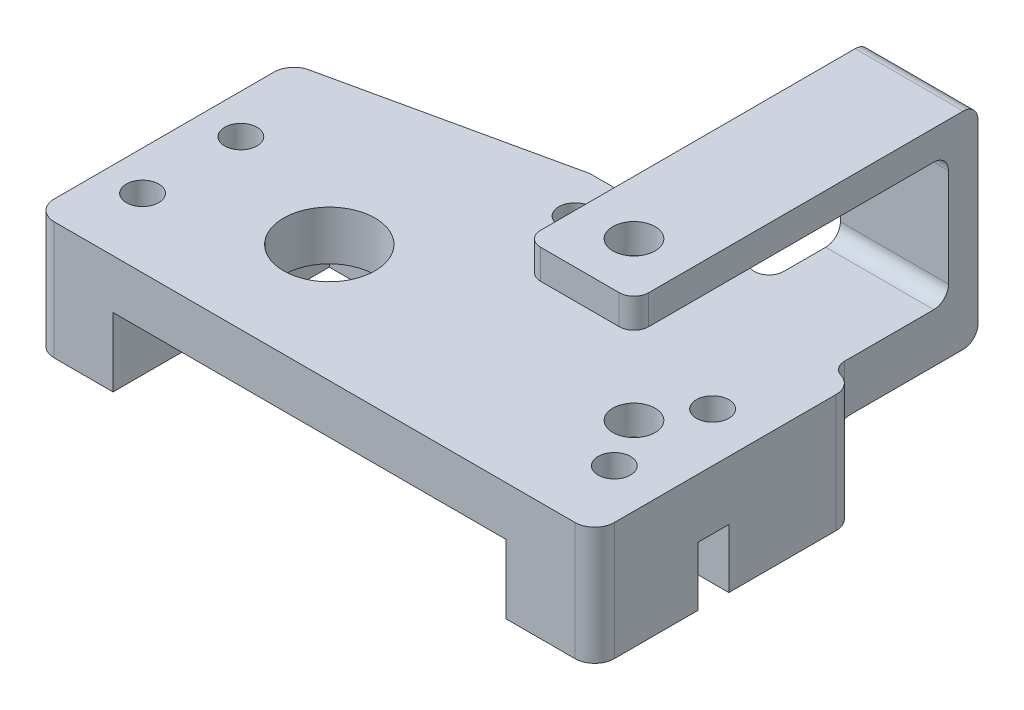
SolidWorks part; units mm, degrees
other "标注1"
sketch "草图14" plane through (64, 22, 26) normal (0.1348, 0.9386, 0.3174) x (-0.9379, 0.0175, 0.3464)
ref_plane "前视基准面" through (0, 0, 0) normal (0, 0, 1) x (1, 0, 0)
ref_plane "上视基准面" through (0, 0, 0) normal (0, 1, 0) x (1, 0, 0)
ref_plane "右视基准面" through (0, 0, 0) normal (1, 0, 0) x (0, 0, -1)
sketch "草图1" plane through (0, 0, 0) normal (0, 1, 0) x (1, 0, 0)
  line L0 (0, 0) -> (25, 5.5)
  line L2 (0, 0) -> (0, -26)
  line L3 (0, -26) -> (8, -26)
  line L4 (57, 0) -> (57, -26)
  line L7 (25, 5.5) -> (41, 5.5)
  line L10 (8, -26) -> (8, -4)
  line L11 (8, -4) -> (48, -4)
  line L12 (48, -26) -> (48, -17)
  line L13 (41, 5.5) -> (57, 0)
  line L14 (48, -26) -> (57, -26)
  line L15 (48, -11) -> (48, -4)
  circle A0 centre (4, -9) radius 1.65
  circle A1 centre (4, -19) radius 1.65
  circle A2 centre (52, -9) radius 1.65
  circle A3 centre (52, -19) radius 1.65
  circle A4 centre (28, 1) radius 1.65
  circle A5 centre (38, 1) radius 1.65
  arc A6 (48, -17) -> (48, -11) centre (49, -14) ccw
  point P12 (25, 5.5)
  point P13 (41, 5.5)
  point P14 (25, 5.5)
  point P15 (0, 0)
  dimension "D6" = 17
  dimension "D7" = 4
  dimension "D8" = 2
  dimension "D10" = 5
  dimension "D11" = 2
  dimension "D12" = 10
  dimension "D13" = 3.3
  dimension "D14" = 48
  dimension "D1" = 26
  dimension "D2" = 57
  dimension "D3" = 40
  dimension "D4" = 22
  dimension "D5" = 8
  dimension "D9" = 2
extrude "凸台-拉伸1" add sketch "草图1" along normal blind 12
sketch "草图2" plane through (0, 0, 0) normal (0, -1, 0) x (-1, 0, 0)
  line L1 (-26.6144, -1.4) -> (-25.2287, 1)
  line L2 (-25.2287, 1) -> (-26.6144, 3.4)
  line L3 (-26.6144, 3.4) -> (-29.3856, 3.4)
  line L4 (-29.3856, 3.4) -> (-30.7713, 1)
  line L5 (-30.7713, 1) -> (-29.3856, -1.4)
  line L6 (-29.3856, -1.4) -> (-26.6144, -1.4)
  line L8 (-41, 5.5) -> (-25, 5.5) construction
  line L9 (-36.6144, -1.4) -> (-35.2287, 1)
  line L10 (-35.2287, 1) -> (-36.6144, 3.4)
  line L11 (-36.6144, 3.4) -> (-39.3856, 3.4)
  line L12 (-39.3856, 3.4) -> (-40.7713, 1)
  line L13 (-40.7713, 1) -> (-39.3856, -1.4)
  line L14 (-39.3856, -1.4) -> (-36.6144, -1.4)
  circle A0 centre (-28, 1) radius 2.4 construction
  dimension "D2" = 4.8
  dimension "D1" = 2
extrude "切除-拉伸1" cut sketch "草图2" against normal blind 8
fillet "圆角1" radius 2 6 edges at (57, 6, 26) (57, 6, 0) (41, 6, -5.5) (25, 6, -5.5) (0, 6, 0) (0, 6, 26)
sketch "草图5" plane through (0, 12, 0) normal (0, 1, 0) x (1, 0, 0)
  line L0 (48, -11) -> (48, -4)
  line L1 (8, -26) -> (48, -26)
  line L2 (8, -26) -> (8, -4)
  line L3 (8, -4) -> (48, -4)
  line L4 (48, -26) -> (48, -17)
  line L5 (0, -1.6078) -> (0, -24) construction
  arc A0 (48, -17) -> (48, -11) centre (49, -14) ccw
  circle A1 centre (28, 1) radius 1.55
  circle A2 centre (38, 1) radius 1.55
  circle A3 centre (49, -14) radius 1.55
  circle A4 centre (18, -14) radius 4.6563
  dimension "D1" = 12
  dimension "D2" = 18
extrude "凸台-拉伸3" add sketch "草图5" against normal blind 5 separate body
sketch "草图6" plane through (0, 7, 0) normal (0, -1, 0) x (-1, 0, 0)
  circle A0 centre (-28, 1) radius 1.55
  circle A1 centre (-38, 1) radius 1.55
sketch "草图7" plane through (0, 7, 0) normal (0, -1, 0) x (-1, 0, 0)
  circle A0 centre (-49, -14) radius 3.15
extrude "切除-拉伸2" cut sketch "草图7" against normal blind 2
sketch "草图8" plane through (0, 0, 0) normal (0, -1, 0) x (-1, 0, 0)
  line L0 (-57, -24) -> (-57, -1.4274) construction
  line L1 (-8, -15.162) -> (0, -15.162)
  line L2 (-8, -15.162) -> (-8, -12.162)
  line L3 (-8, -12.162) -> (0, -12.162)
  line L4 (0, -15.162) -> (0, -12.162)
  line L5 (-51.7, -12.3538) -> (-57, -12.3538)
  line L6 (-51.7, -12.3538) -> (-51.7, -15.4875)
  line L7 (-51.7, -15.4875) -> (-57, -15.4875)
  line L8 (-57, -12.3538) -> (-57, -15.4875)
  line L9 (-8, -26) -> (-8, -4) construction
  arc A0 (-48, -11) -> (-48, -17) centre (-49, -14) ccw construction
  dimension "D2" = 8
  dimension "D1" = 3
extrude "切除-拉伸3" cut sketch "草图8" against normal blind 6
extrude "切除-拉伸4" cut sketch "草图6" against normal blind 10
sketch "草图17" plane through (0, 0, -5.5) normal (0, 0, -1) x (-1, 0, 0)
  line L0 (-55.6502, 12) -> (-41.316, 12) construction
  line L1 (-43.5, 12) -> (-54.5, 12)
  line L2 (-43.5, 12) -> (-43.5, 9)
  line L3 (-43.5, 9) -> (-54.5, 7)
  line L4 (-54.5, 12) -> (-54.5, 7)
  dimension "D1" = 3
extrude "凸台-拉伸9" add sketch "草图17" along normal blind 10 and the other way blind 10
sketch "草图18" plane through (0, 12, 0) normal (0, 1, 0) x (1, 0, 0)
  line L0 (54.5, 0.8594) -> (54.5, 15.5) construction
  line L1 (43.5, 15.5) -> (54.5, 15.5)
  line L2 (43.5, 15.5) -> (43.5, 12.5)
  line L3 (43.5, 12.5) -> (54.5, 12.5)
  line L4 (54.5, 15.5) -> (54.5, 12.5)
  dimension "D1" = 3
extrude "凸台-拉伸10" add sketch "草图18" along normal blind 16
sketch "草图19" plane through (0, 0, -12.5) normal (0, 0, 1) x (1, 0, 0)
  line L0 (54.5, 28) -> (54.5, 12) construction
  line L1 (43.5, 28) -> (54.5, 28)
  line L2 (43.5, 28) -> (43.5, 25)
  line L3 (43.5, 25) -> (54.5, 25)
  line L4 (54.5, 28) -> (54.5, 25)
  dimension "D1" = 3
extrude "凸台-拉伸11" add sketch "草图19" along normal blind 32
sketch "草图20" plane through (0, 28, 0) normal (0, 1, 0) x (1, 0, 0)
  circle A0 centre (49, -14) radius 2.15
  circle A1 centre (49, -14) radius 1.55 construction
extrude "切除-拉伸7" cut sketch "草图20" against normal blind 22
fillet "圆角4" radius 1.5 9 edges at (54.5, 9.5, -0.8594) (54.5, 26.5, 19.5) (43.5, 26.5, 19.5) (49, 25, -12.5) (49, 28, -15.5) (49, 12, -12.5) (49, 8, -15.5) (49, 8, -2.75) (43.5, 10.5, -4.6406)
